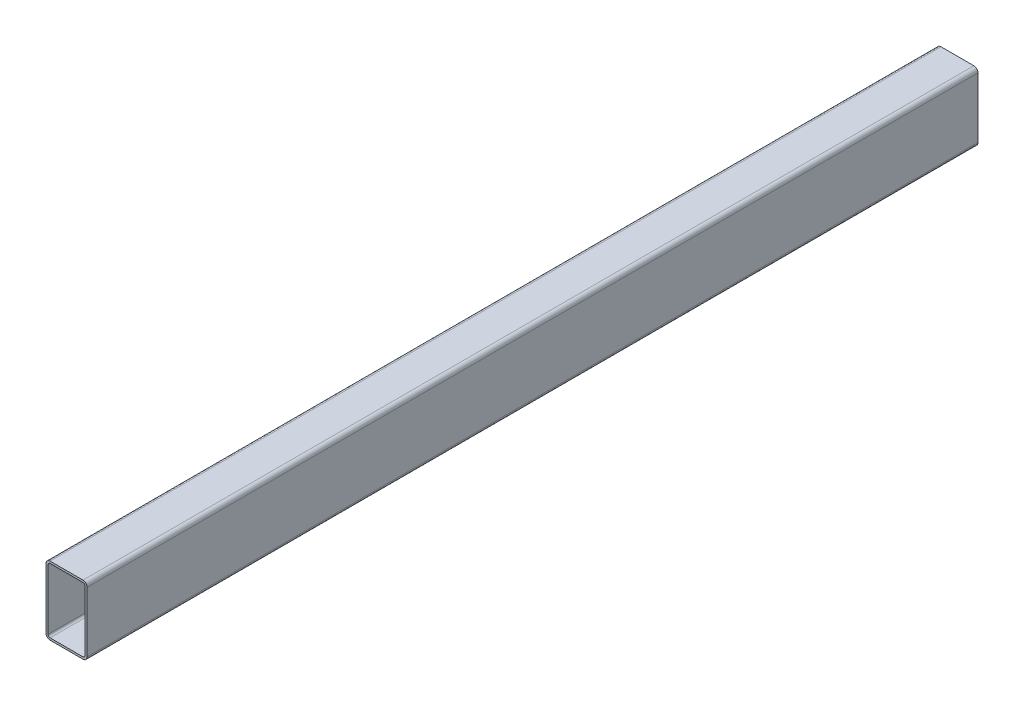
SolidWorks part; units mm, degrees
ref_plane "Front Plane" through (0, 0, 0) normal (0, 0, 1) x (1, 0, 0)
ref_plane "Top Plane" through (0, 0, 0) normal (0, 1, 0) x (1, 0, 0)
ref_plane "Right Plane" through (0, 0, 0) normal (1, 0, 0) x (0, 0, -1)
sketch "Sketch1" plane through (0, 0, 0) normal (0, 0, 1) x (1, 0, 0)
  line L0 (-24, 47) -> (24, 47)
  line L1 (-24, -50) -> (24, -50)
  line L2 (-30, -44) -> (-30, 44)
  line L3 (-24, 50) -> (24, 50)
  line L4 (30, -44) -> (30, 44)
  line L5 (-30, -50) -> (30, 50) construction
  line L6 (-30, 50) -> (30, -50) construction
  line L7 (27, -44) -> (27, 44)
  line L8 (-24, -47) -> (24, -47)
  line L9 (-27, -44) -> (-27, 44)
  arc A0 (-24, -50) -> (-30, -44) centre (-24, -44) cw
  arc A1 (24, -50) -> (30, -44) centre (24, -44) ccw
  arc A2 (24, 50) -> (30, 44) centre (24, 44) cw
  arc A3 (-30, 44) -> (-24, 50) centre (-24, 44) cw
  arc A4 (24, 47) -> (27, 44) centre (24, 44) cw
  arc A5 (24, -47) -> (27, -44) centre (24, -44) ccw
  arc A6 (-24, -47) -> (-27, -44) centre (-24, -44) cw
  arc A7 (-27, 44) -> (-24, 47) centre (-24, 44) cw
  point P0 (0, 0)
  dimension "D3" = 6
  dimension "D1" = 60
  dimension "D2" = 100
  dimension "D4" = 3
extrude "Boss-Extrude1" add sketch "Sketch1" along normal mid plane 1300
